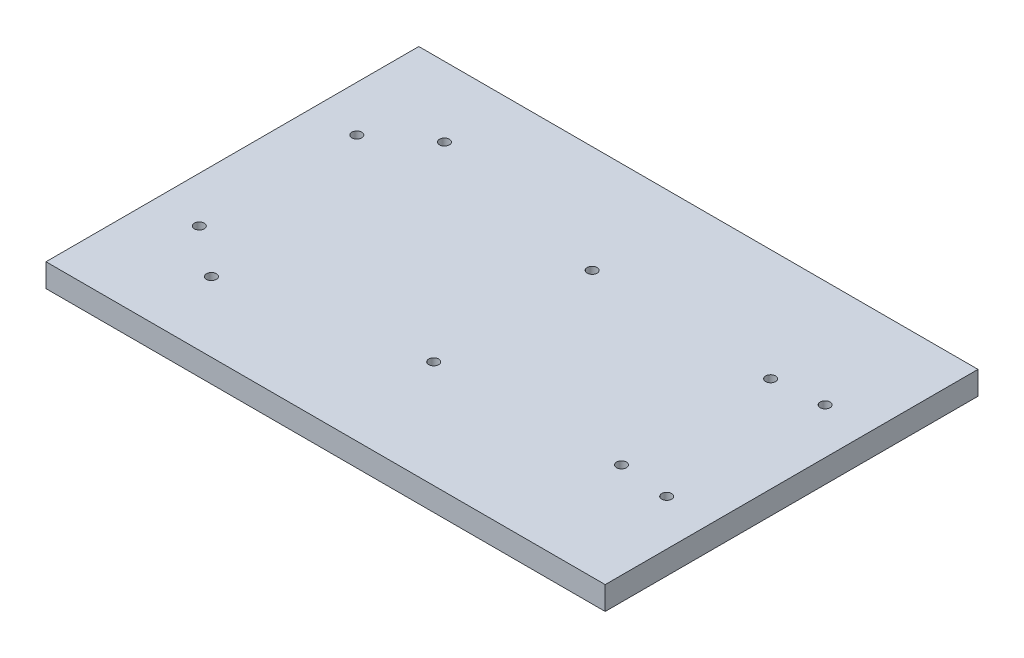
SolidWorks part; units mm, degrees
ref_plane "Front Plane" through (0, 0, 0) normal (0, 0, 1) x (1, 0, 0)
ref_plane "Top Plane" through (0, 0, 0) normal (0, 1, 0) x (1, 0, 0)
ref_plane "Right Plane" through (0, 0, 0) normal (1, 0, 0) x (0, 0, -1)
sketch "Sketch1" plane through (0, 0, 0) normal (0, 1, 0) x (1, 0, 0)
  line L0 (0.254, 21.463) -> (0.254, -21.463)
  line L1 (63.754, -21.463) -> (-63.754, -21.463)
  line L2 (63.754, -21.463) -> (63.754, 21.463)
  line L3 (63.754, 21.463) -> (-63.754, 21.463)
  line L4 (-63.754, -21.463) -> (-63.754, 21.463)
  line L5 (63.754, -21.463) -> (-63.754, 21.463) construction
  line L6 (63.754, 21.463) -> (-63.754, -21.463) construction
  line L8 (76.2, -50.8) -> (-76.2, -50.8)
  line L9 (76.2, -50.8) -> (76.2, 50.8)
  line L10 (76.2, 50.8) -> (-76.2, 50.8)
  line L11 (-76.2, -50.8) -> (-76.2, 50.8)
  line L12 (76.2, -50.8) -> (-76.2, 50.8) construction
  line L13 (76.2, 50.8) -> (-76.2, -50.8) construction
  point P0 (0, 0)
  point P8 (0, 0)
  dimension "D1" = 127.508
  dimension "D2" = 42.926
  dimension "D3" = 63.5
  dimension "D4" = 152.4
  dimension "D5" = 101.6
extrude "Boss-Extrude1" add sketch "Sketch1" against normal blind 6.35 contours L11 L8 L9 L10 L1 L4 L3 L2 | L4 L1 L0 L3 | L2 L3 L0 L1
hole_wizard "Tap Drill for #6-32 Tap2" positions "3DSketch5" profile "Sketch4" hole size "#6-32" standard "ANSI Inch" end condition through all
sketch3d "3DSketch5"
  line L6 (-63.7539, 0, -21.463) -> (-63.7539, 0, 21.463)
  line L8 (-63.7539, 0, 0) -> (0, 0, 0)
  line L10 (63.754, 0, -21.59) -> (63.754, 0, 21.59)
  line L12 (0.254, 0, -21.5903) -> (0.254, 0, 21.5897)
  line L15 (0, 0, 0) -> (63.754, 0, 0)
  point P0 (-63.7539, 0, -21.463)
  point P2 (0.254, 0, -21.5903)
  point P4 (63.754, 0, -21.59)
  point P6 (63.754, 0, 21.59)
  point P8 (0.254, 0, 21.5897)
  point P10 (-63.7539, 0, 21.463)
  dimension "D1" = 63.5
  dimension "D2" = 64.008
  dimension "D3" = 42.926
  dimension "D4" = 43.18
  dimension "D5" = 43.18
sketch "Sketch4" plane through (-63.7539, 0, -21.463) normal (1, 0, 0) x (0, 0, 1)
  line L0 (0, 0) -> (0, 6.35)
  line L1 (0, 6.35) -> (1.3525, 6.35)
  line L2 (1.3525, 6.35) -> (1.3525, 0)
  line L5 (1.3525, 0) -> (0, 0)
  line L11 (0, -6.35) -> (0, 107.95) construction
  dimension "Thru Hole Dia." = 2.7051
  dimension "Thru Hole Depth" = 6.35
hole_wizard "Tap Drill for #6-32 Tap5" positions "3DSketch8" profile "Sketch7" hole size "#6-32" standard "ANSI Inch" end condition through all
sketch3d "3DSketch8"
  line L0 (-50.165, 0, -31.75) -> (-50.165, 0, 31.75)
  line L2 (50.165, 0, -20.32) -> (50.165, 0, 20.32)
  line L4 (-50.165, 0, 0) -> (0, 0, 0)
  line L5 (0, 0, 0) -> (50.165, 0, 0)
  point P0 (-50.165, 0, -31.75)
  point P2 (-50.165, 0, 31.75)
  point P4 (50.165, 0, 20.32)
  point P6 (50.165, 0, -20.32)
  point P22 (0, 0, 0)
  point P23 (0, 0, 0)
  dimension "D1" = 63.5
  dimension "D2" = 100.33
  dimension "D3" = 50.165
  dimension "D4" = 40.64
sketch "Sketch7" plane through (-50.165, 0, -31.75) normal (1, 0, 0) x (0, 0, 1)
  line L0 (0, 0) -> (0, 6.35)
  line L1 (0, 6.35) -> (1.3525, 6.35)
  line L2 (1.3525, 6.35) -> (1.3525, 0)
  line L5 (1.3525, 0) -> (0, 0)
  line L11 (0, -6.35) -> (0, 107.95) construction
  dimension "Thru Hole Dia." = 2.7051
  dimension "Thru Hole Depth" = 6.35
